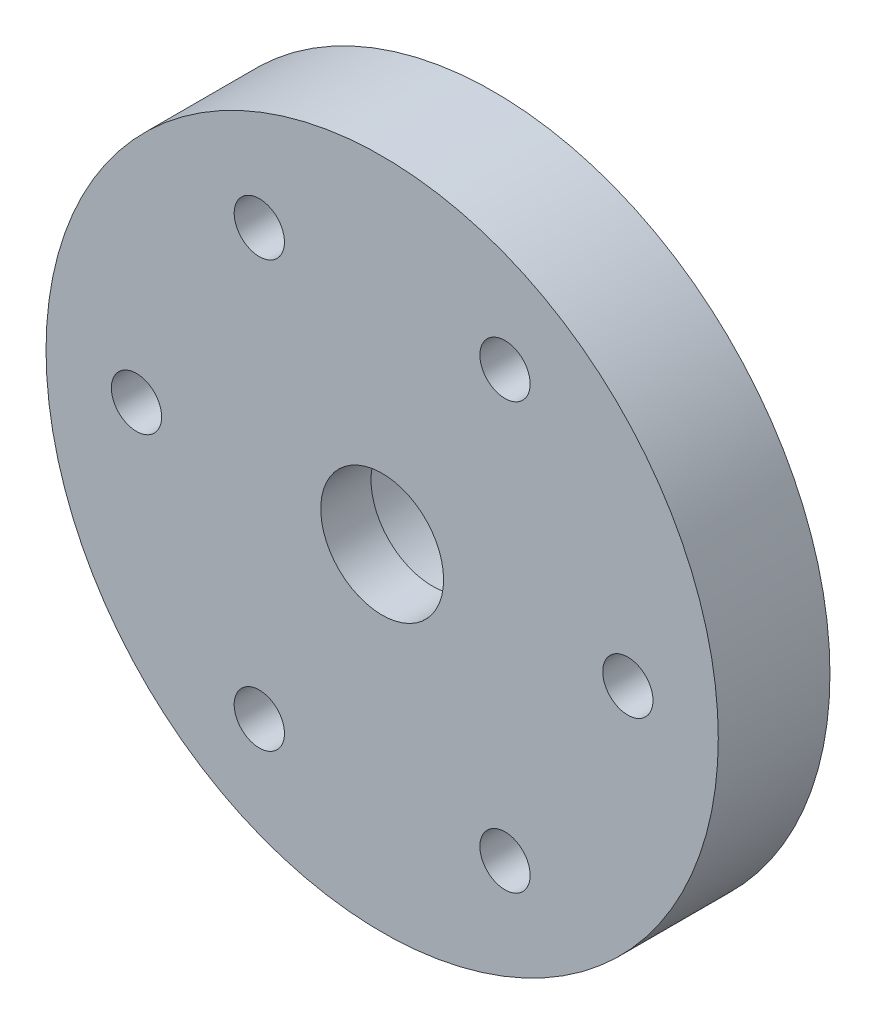
SolidWorks part; units mm, degrees
ref_plane "Plan de face" through (0, 0, 0) normal (0, 0, 1) x (1, 0, 0)
ref_plane "Plan de dessus" through (0, 0, 0) normal (0, 1, 0) x (1, 0, 0)
ref_plane "Plan de droite" through (0, 0, 0) normal (1, 0, 0) x (0, 0, -1)
sketch "Esquisse1" plane through (0, 0, 0) normal (0, 0, 1) x (1, 0, 0)
  line L0 (0, 0) -> (22, 0) construction
  line L1 (0, 0) -> (11, -19.0526) construction
  line L2 (0, 0) -> (-11, -19.0526) construction
  line L3 (0, 0) -> (-22, 0) construction
  line L4 (0, 0) -> (-11, 19.0526) construction
  line L5 (0, 0) -> (11, 19.0526) construction
  line L11 (23.5, -23.55) -> (-23.5, 23.55) construction
  line L12 (23.5, 23.55) -> (-23.5, -23.55) construction
  circle A0 centre (22, 0) radius 2.25
  circle A1 centre (11, -19.0526) radius 2.25
  circle A2 centre (-11, -19.0526) radius 2.25
  circle A3 centre (-22, 0) radius 2.25
  circle A4 centre (-11, 19.0526) radius 2.25
  circle A5 centre (11, 19.0526) radius 2.25
  circle A10 centre (0, 0) radius 30.1
  circle A11 centre (0, 0) radius 8.1
  point P17 (0, 0)
  dimension "D5" = 4.5
  dimension "D10" = 60.2
  dimension "D11" = 16.2
  dimension "D1" = 22
  dimension "D3" = 47
  dimension "D4" = 47.1
  dimension "D2" = 6
extrude "Boss.-Extru.1" add sketch "Esquisse1" along normal blind 10
sketch "Esquisse2" plane through (0, 0, 10) normal (0, 0, 1) x (1, 0, 0)
  circle A0 centre (0, 0) radius 8.1
  circle A1 centre (0, 0) radius 5.5
  dimension "D1" = 11
extrude "Boss.-Extru.2" add sketch "Esquisse2" against normal blind 4.5
